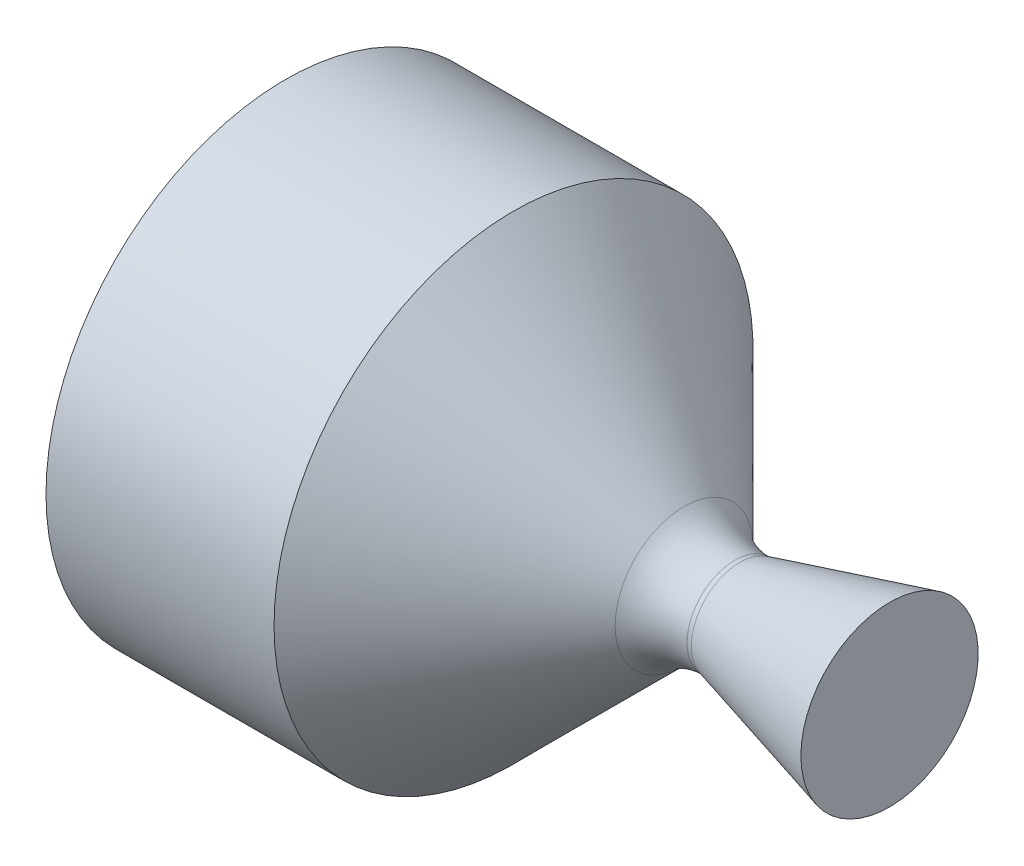
SolidWorks part; units mm, degrees
ref_plane "Front Plane" through (0, 0, 0) normal (0, 0, 1) x (1, 0, 0)
ref_plane "Top Plane" through (0, 0, 0) normal (0, 1, 0) x (1, 0, 0)
ref_plane "Right Plane" through (0, 0, 0) normal (1, 0, 0) x (0, 0, -1)
sketch "Sketch1" plane through (0, 0, 0) normal (0, 0, 1) x (1, 0, 0)
  line L0 (-13.3606, 28.0607) -> (13.3606, 28.0607)
  line L1 (0, 0) -> (50000, 0) construction
  line L2 (13.3606, 28.0607) -> (33.3436, 8.0777)
  line L3 (39.2962, 5.6121) -> (39.3062, 5.6121)
  line L5 (39.8872, 5.6886) -> (57.4196, 10.3864)
  line L8 (-13.3606, 28.0607) -> (-13.3606, 0)
  line L9 (-13.3606, 0) -> (57.4196, 0)
  line L10 (57.4196, 10.3864) -> (57.4196, 0)
  arc A0 (39.3062, 5.6121) -> (39.8872, 5.6886) centre (39.3062, 7.8569) ccw
  arc A1 (33.3436, 8.0777) -> (39.2962, 5.6121) centre (39.2962, 14.0303) ccw
  point P2 (0, 28.0607)
  point P12 (39.6017, 5.6121)
  point P16 (35.8093, 5.6121)
  dimension "D8" = 2.2448
  dimension "D9" = 8.4182
  dimension "D1" = 28.0607
  dimension "D2" = 26.7213
  dimension "D3" = 135
  dimension "D4" = 5.6121
  dimension "D5" = 3.7925
  dimension "D6" = 10.3864
  dimension "D7" = 165
revolve "Revolve1" add sketch "Sketch1" angle 360 about L1
equation "\"Rc\" = 28.0607mm"
equation "\"Rt\" = 5.6121mm"
equation "\"Re\" = 10.3864mm"
equation "\"Lcyl\"= 26.7213mm"
equation "\"R_up\"= 1.5 * \"Rt\""
equation "\"R_down\"= 0.4 * \"Rt\""
equation "\"L_throat\"= \"R_up\" * tan(22.5) + \"R_down\" * tan(7.5) + 0.01mm"
equation "\"D1@Sketch1\" = \"Rc\""
equation "\"D2@Sketch1\" = \"Lcyl\""
equation "\"D4@Sketch1\" = \"Rt\""
equation "\"D5@Sketch1\" = \"L_throat\""
equation "\"D6@Sketch1\" = \"Re\""
equation "\"D8@Sketch1\" = \"R_down\""
equation "\"D9@Sketch1\" = \"R_up\""
